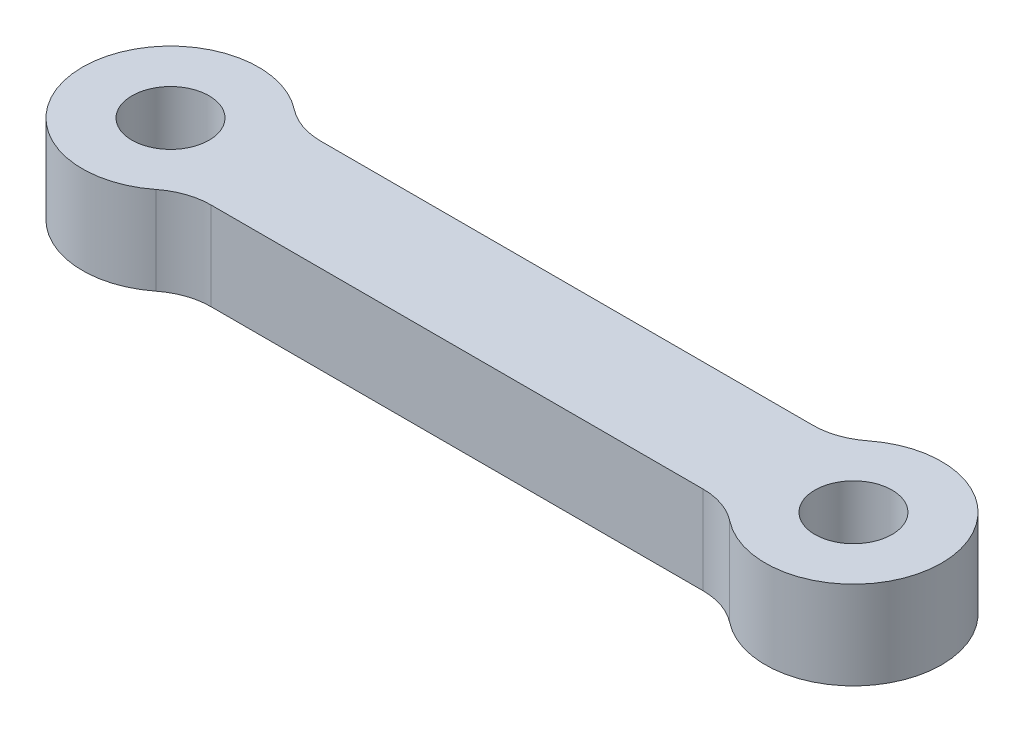
SolidWorks part; units mm, degrees
ref_plane "Front Plane" through (0, 0, 0) normal (0, 0, 1) x (1, 0, 0)
ref_plane "Top Plane" through (0, 0, 0) normal (0, 1, 0) x (1, 0, 0)
ref_plane "Right Plane" through (0, 0, 0) normal (1, 0, 0) x (0, 0, -1)
sketch "Sketch1" plane through (0, 0, 0) normal (0, 1, 0) x (1, 0, 0)
  line L0 (3.1225, -2.5) -> (27.8775, -2.5)
  line L1 (0, 0) -> (31, 0) construction
  line L2 (3.1225, 2.5) -> (27.8775, 2.5)
  circle A0 centre (0, 0) radius 4
  circle A1 centre (0, 0) radius 1.75
  circle A2 centre (31, 0) radius 4
  circle A3 centre (31, 0) radius 1.75
  arc A4 (3.1225, -2.5) -> (3.1225, 2.5) centre (0, 0) ccw
  arc A5 (27.8775, -2.5) -> (27.8775, 2.5) centre (31, 0) cw
  dimension "D1" = 3.5
  dimension "D3" = 8
  dimension "D2" = 31
  dimension "D4" = 5
extrude "Boss-Extrude1" add sketch "Sketch1" along normal blind 4 contours A5 L2 A4 L0 | A0 | A1 | A2 | A3
fillet "Fillet1" radius 3 4 edges at (3.1225, 2, 2.5) (3.1225, 2, -2.5) (27.8775, 2, -2.5) (27.8775, 2, 2.5)
